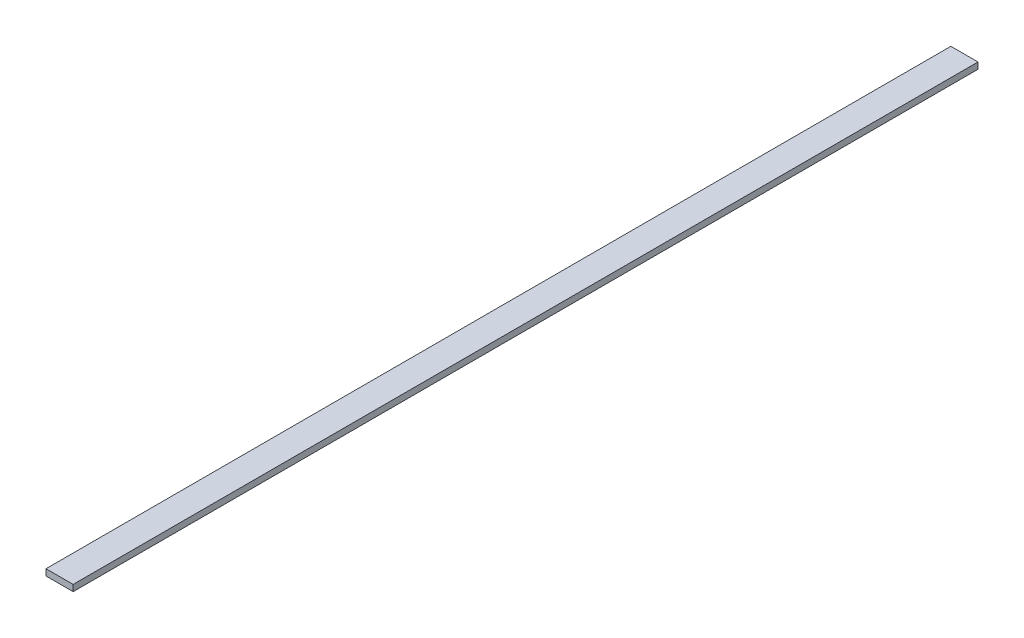
SolidWorks part; units mm, degrees
ref_plane "Front Plane" through (0, 0, 0) normal (0, 0, 1) x (1, 0, 0)
ref_plane "Top Plane" through (0, 0, 0) normal (0, 1, 0) x (1, 0, 0)
ref_plane "Right Plane" through (0, 0, 0) normal (1, 0, 0) x (0, 0, -1)
sketch "Sketch1" plane through (0, 0, 0) normal (0, 0, 1) x (1, 0, 0)
  line L0 (-0.8009, 0.4698) -> (2.1991, 0.4698)
  line L1 (2.1991, 0.4698) -> (2.1991, -0.2302)
  line L2 (2.1991, -0.2302) -> (-0.8009, -0.2302)
  line L3 (-0.8009, -0.2302) -> (-0.8009, 0.4698)
  dimension "D1" = 0.7
  dimension "D2" = 3
extrude "Boss-Extrude1" add sketch "Sketch1" along normal blind 100
